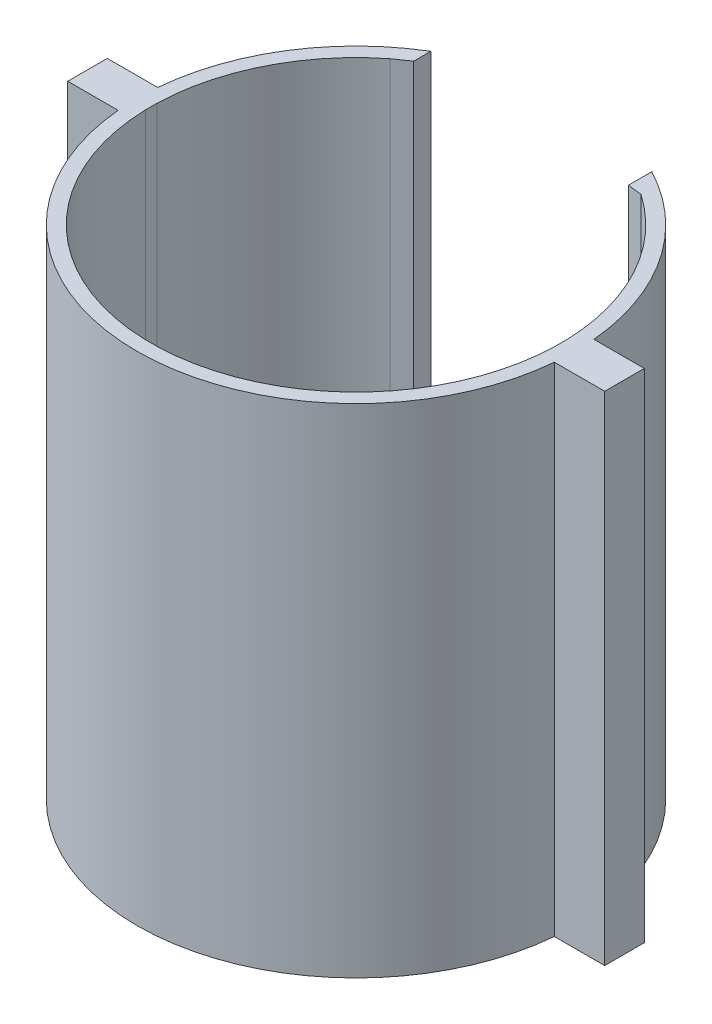
SolidWorks part; units mm, degrees
ref_plane "Front Plane" through (0, 0, 0) normal (0, 0, 1) x (1, 0, 0)
ref_plane "Top Plane" through (0, 0, 0) normal (0, 1, 0) x (1, 0, 0)
ref_plane "Right Plane" through (0, 0, 0) normal (1, 0, 0) x (0, 0, -1)
sketch "Sketch1" plane through (0, 0, 0) normal (0, 1, 0) x (1, 0, 0)
  line L1 (-24.13, -1.778) -> (24.13, -1.778)
  line L2 (-24.13, -1.778) -> (-24.13, 1.778)
  line L3 (-24.13, 1.778) -> (24.13, 1.778)
  line L4 (24.13, -1.778) -> (24.13, 1.778)
  line L5 (-24.13, -1.778) -> (24.13, 1.778) construction
  line L6 (-24.13, 1.778) -> (24.13, -1.778) construction
  line L7 (-10.1451, 20.1672) -> (9.1589, 20.1672)
  line L8 (-10.1451, 20.1672) -> (-10.1451, 11.5592)
  line L9 (-10.1451, 11.5592) -> (9.1589, 11.5592)
  line L10 (9.1589, 20.1672) -> (9.1589, 11.5592)
  circle A0 centre (0, 0) radius 19.685
  dimension "D1" = 39.37
  dimension "D2" = 48.26
  dimension "D3" = 3.556
  dimension "D4" = 19.304
extrude "Boss-Extrude1" add sketch "Sketch1" along normal blind 44.704 contours L1 A0 | A0 L3 L2 L1 | A0 L1 L4 L3 | L1 A0 L3 | L3 A0 L10 L9 L8
sketch "Sketch3" plane through (0, 44.704, 0) normal (0, 1, 0) x (1, 0, 0)
  line L18 (-18.408, 0.508) -> (-18.408, -0.508)
  line L19 (18.408, 0.508) -> (18.408, -0.508)
  line L27 (18.408, -0.508) -> (22.86, -0.508)
  line L28 (22.86, -0.508) -> (22.86, 0.508)
  line L29 (22.86, 0.508) -> (18.408, 0.508)
  line L30 (10.4289, 15.1773) -> (10.4289, 10.2892)
  line L31 (10.4289, 10.2892) -> (-11.4151, 10.2892)
  line L32 (-11.4151, 10.2892) -> (-11.4151, 14.4502)
  line L33 (-18.408, 0.508) -> (-22.86, 0.508)
  line L34 (-22.86, 0.508) -> (-22.86, -0.508)
  line L35 (-22.86, -0.508) -> (-18.408, -0.508)
  line L39 (10.4289, 15.1773) -> (10.4289, 10.2892)
  line L40 (10.4289, 10.2892) -> (-11.4151, 10.2892)
  line L41 (-11.4151, 10.2892) -> (-11.4151, 14.4502)
  arc A9 (-18.408, -0.508) -> (18.408, -0.508) centre (0, 0) ccw
  arc A10 (18.408, 0.508) -> (10.4289, 15.1773) centre (0, 0) ccw
  arc A11 (-11.4151, 14.4502) -> (-18.408, 0.508) centre (0, 0) ccw
  arc A12 (-18.408, -0.508) -> (18.408, -0.508) centre (0, 0) ccw
  arc A13 (18.408, 0.508) -> (10.4289, 15.1773) centre (0, 0) ccw
  arc A14 (-11.4151, 14.4502) -> (-18.408, 0.508) centre (0, 0) ccw
  dimension "D1" = 1.27
extrude "Cut-Extrude1" cut sketch "Sketch3" against normal through all
sketch "Sketch4" plane through (0, 44.704, 0) normal (0, 1, 0) x (1, 0, 0)
  line L0 (-11.4151, 14.4502) -> (-10.1451, 15.3343)
  line L1 (-10.1451, 16.8694) -> (-10.1451, 11.5592) construction
  line L2 (-10.1451, 15.3343) -> (9.1589, 15.3343)
  line L3 (9.1589, 17.4245) -> (9.1589, 11.5592) construction
  line L4 (9.1589, 15.3343) -> (10.4289, 15.1773)
  line L5 (10.4289, 15.1773) -> (10.4289, 10.2892)
  line L6 (10.4289, 10.2892) -> (-11.4151, 10.2892)
  line L7 (-11.4151, 10.2892) -> (-11.4151, 14.4502)
extrude "Cut-Extrude2" cut sketch "Sketch4" against normal through all
